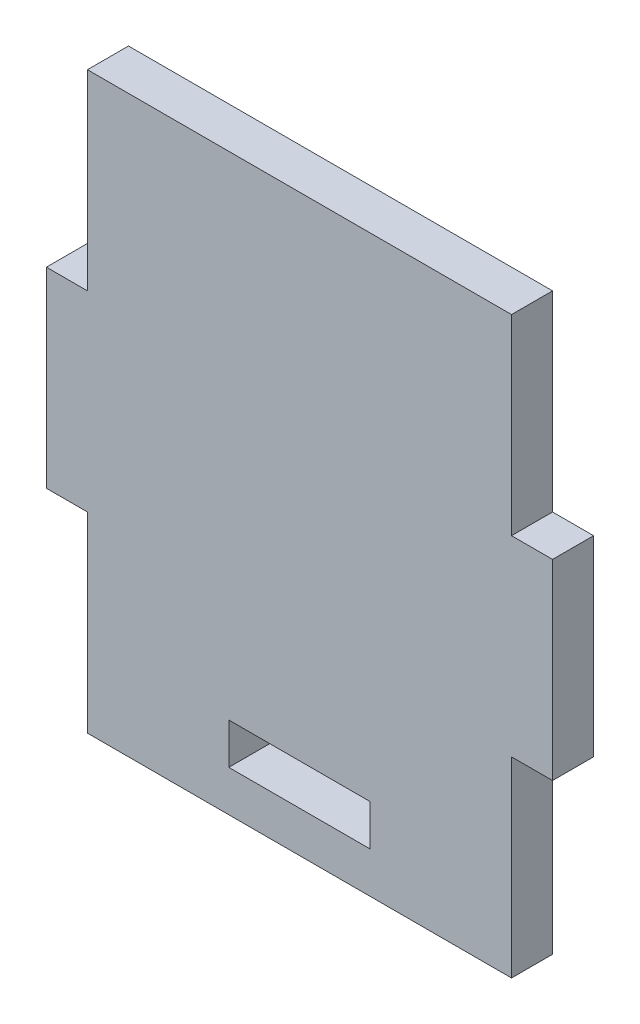
SolidWorks part; units mm, degrees
ref_plane "Plan de face" through (0, 0, 0) normal (0, 0, 1) x (1, 0, 0)
ref_plane "Plan de dessus" through (0, 0, 0) normal (0, 1, 0) x (1, 0, 0)
ref_plane "Plan de droite" through (0, 0, 0) normal (1, 0, 0) x (0, 0, -1)
sketch "Esquisse1" plane through (0, 0, 0) normal (0, 0, 1) x (1, 0, 0)
  line L0 (0, 42) -> (0, 0)
  line L1 (0, 0) -> (31, 0)
  line L3 (0, 42) -> (31, 42)
  line L4 (31, 0) -> (31, 42)
  line L5 (0, 28) -> (-3, 28)
  line L6 (-3, 28) -> (-3, 14)
  line L7 (31, 28) -> (34, 28)
  line L9 (31, 14) -> (34, 14)
  line L10 (34, 28) -> (34, 14)
  line L11 (-3, 14) -> (0, 14)
  line L12 (0, 0) -> (31, 0)
  line L13 (0, 28) -> (-3, 28)
  line L15 (0, 14) -> (-3, 14)
  line L16 (-3, 28) -> (-3, 14)
  line L17 (0, 0) -> (0, 14)
  line L18 (0, 42) -> (0, 28)
  line L19 (10.33, 3) -> (20.67, 3)
  line L20 (10.33, 3) -> (10.33, 6)
  line L21 (10.33, 6) -> (20.67, 6)
  line L22 (20.67, 3) -> (20.67, 6)
extrude "Boss.-Extru.1" add sketch "Esquisse1" along normal blind 3 contours L1 L4 L3 L0 L22 L19 L20 L21 | L6 L11 L0 L5 | L10 L7 L4 L9
